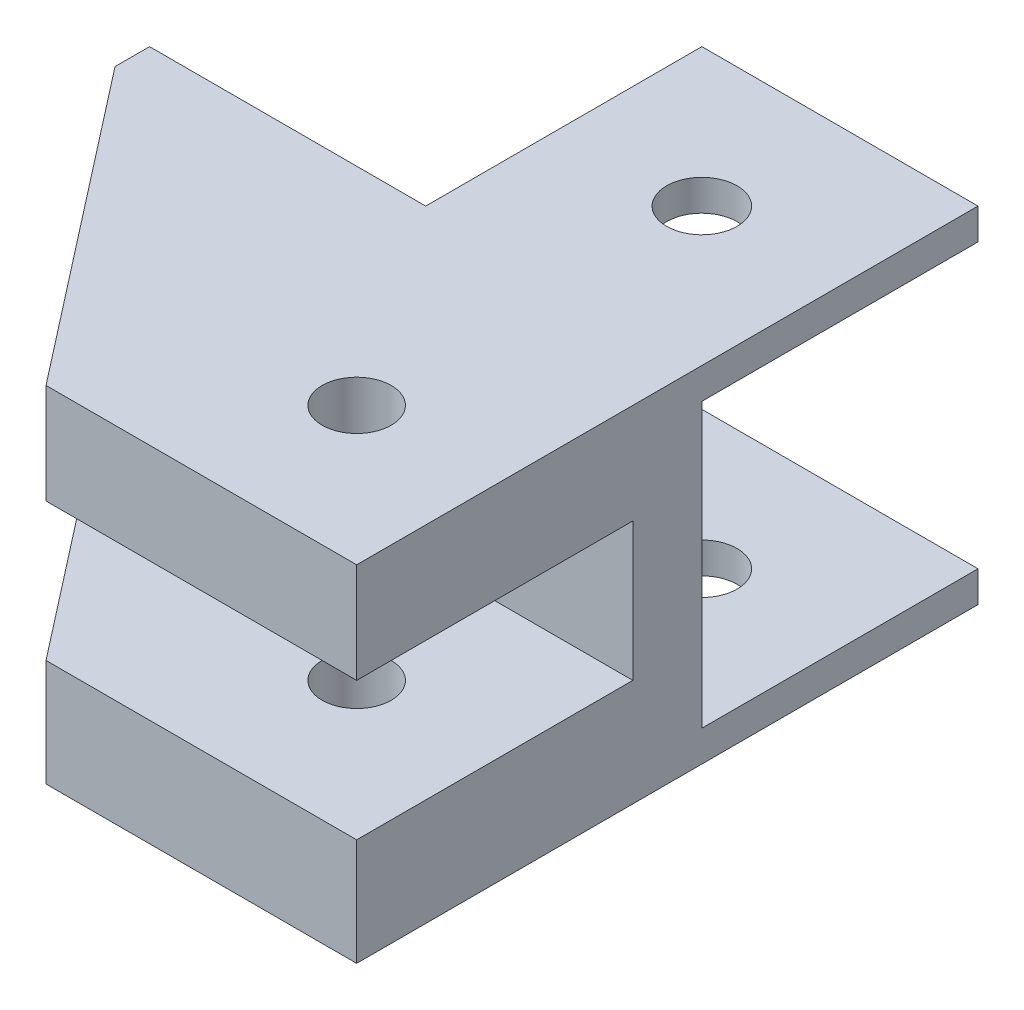
SolidWorks part; units mm, degrees
ref_plane "Front Plane" through (0, 0, 0) normal (0, 0, 1) x (1, 0, 0)
ref_plane "Top Plane" through (0, 0, 0) normal (0, 1, 0) x (1, 0, 0)
ref_plane "Right Plane" through (0, 0, 0) normal (1, 0, 0) x (0, 0, -1)
sketch "Sketch2" plane through (0, 0, 0) normal (1, 0, 0) x (0, 0, -1)
  line L1 (0, 0) -> (45, 0)
  line L2 (0, 0) -> (0, 25)
  line L3 (0, 25) -> (45, 25)
  line L4 (45, 0) -> (45, 25)
  line L8 (25, 22.75) -> (25, 2.25)
  line L9 (20, 22.75) -> (20, 2.25)
  line L10 (0, 22.75) -> (45, 22.75)
  line L11 (0, 2.25) -> (45, 2.25)
  line L12 (20, 17.75) -> (0, 17.75)
  line L13 (20, 7.75) -> (0, 7.75)
  dimension "D1" = 45
  dimension "D2" = 25
  dimension "D3" = 20
  dimension "D4" = 20
  dimension "D5" = 10
  dimension "D6" = 5
  dimension "D7" = 2.25
  dimension "D8" = 2.25
extrude "Boss-Extrude1" add sketch "Sketch2" along normal blind 20 contours L9 L11 L8 L10 | L2 L10 L4 L3 | L11 L2 L1 L4 | L12 L9 L10 L2 | L9 L13 L2 L11
sketch "Sketch3" plane through (0, 25, 0) normal (0, 1, 0) x (1, 0, 0)
  line L0 (10, 45) -> (10, 0) construction
  line L1 (0, 22.5) -> (20, 22.5) construction
  line L2 (0, 10) -> (20, 10) construction
  line L3 (20, 35) -> (0, 35) construction
  line L4 (0, 45) -> (0, 0)
  line L5 (0, 0) -> (20, 0)
  line L6 (20, 0) -> (20, 45)
  line L7 (20, 45) -> (0, 45)
  line L8 (0, 45) -> (0, 0)
  line L9 (0, 0) -> (20, 0)
  line L10 (20, 0) -> (20, 45)
  line L11 (20, 45) -> (0, 45)
  circle A0 centre (10, 10) radius 2.5
  circle A1 centre (10, 35) radius 2.55
  dimension "D3" = 5
  dimension "D5" = 5.1
  dimension "D2" = 10
  dimension "D4" = 10
  dimension "D1" = 0
extrude "Cut-Extrude1" cut sketch "Sketch3" against normal through all contours A0 | A1
sketch "Sketch5" plane through (0, 0, 0) normal (-1, 0, 0) x (0, 0, 1)
  line L0 (-25, 22.75) -> (-25, 25)
  line L1 (-25, 2.25) -> (-25, 0)
  line L12 (-20, 7.75) -> (-20, 17.75)
  line L13 (-20, 17.75) -> (0, 17.75)
  line L14 (0, 17.75) -> (0, 25)
  line L15 (0, 25) -> (-45, 25)
  line L16 (-45, 25) -> (-45, 22.75)
  line L17 (-45, 22.75) -> (-25, 22.75)
  line L18 (-25, 22.75) -> (-25, 2.25)
  line L19 (-25, 2.25) -> (-45, 2.25)
  line L20 (-45, 2.25) -> (-45, 0)
  line L21 (-45, 0) -> (0, 0)
  line L22 (0, 0) -> (0, 7.75)
  line L23 (0, 7.75) -> (-20, 7.75)
  line L24 (-20, 7.75) -> (-20, 17.75)
  line L25 (-20, 17.75) -> (0, 17.75)
  line L26 (0, 17.75) -> (0, 25)
  line L27 (0, 25) -> (-45, 25)
  line L28 (-45, 25) -> (-45, 22.75)
  line L29 (-45, 22.75) -> (-25, 22.75)
  line L30 (-25, 22.75) -> (-25, 2.25)
  line L31 (-25, 2.25) -> (-45, 2.25)
  line L32 (-45, 2.25) -> (-45, 0)
  line L33 (-45, 0) -> (0, 0)
  line L34 (0, 0) -> (0, 7.75)
  line L35 (0, 7.75) -> (-20, 7.75)
  line M13 (-20, 7.75) -> (-20, 17.75)
  line M14 (-20, 17.75) -> (0, 17.75)
  line M15 (0, 17.75) -> (0, 25)
  line M16 (0, 25) -> (-45, 25)
  line M19 (-25, 22.75) -> (-25, 2.25)
  line M22 (-45, 0) -> (0, 0)
  line M23 (0, 0) -> (0, 7.75)
  line M24 (0, 7.75) -> (-20, 7.75)
  dimension "D1" = 0
extrude "Boss-Extrude2" add sketch "Sketch5" along normal blind 20 contours L1 L0 M19 M22 M23 M24 M13 M14 M15 M16
sketch "Sketch6" plane through (0, 0, 0) normal (0, -1, 0) x (1, 0, 0)
  line L0 (0, -25) -> (0, 0) construction
  line L1 (-2.5, 0) -> (-20, -22.5)
  line L6 (20, 0) -> (-20, 0)
  line L7 (-20, 0) -> (-20, -25)
  line L8 (-20, -25) -> (0, -25)
  line L9 (0, -25) -> (0, -45)
  line L10 (0, -45) -> (20, -45)
  line L11 (20, -45) -> (20, 0)
  line L12 (20, 0) -> (-20, 0)
  line L13 (-20, 0) -> (-20, -25)
  line L14 (-20, -25) -> (0, -25)
  line L15 (0, -25) -> (0, -45)
  line L16 (0, -45) -> (20, -45)
  line L17 (20, -45) -> (20, 0)
  line M9 (20, 0) -> (-20, 0)
  line M10 (-20, 0) -> (-20, -25)
  dimension "D2" = 2.5
  dimension "D3" = 2.5
  dimension "D1" = 0
extrude "Cut-Extrude2" cut sketch "Sketch6" against normal through all contours L1 M9 M10
sketch "Sketch7" plane through (0, 0, -20) normal (0, 0, 1) x (1, 0, 0)
  line L0 (0, 24.7346) -> (0, 0) construction
  line L1 (0, 0) -> (-20, 0)
  line L2 (-10, 0) -> (-10, 25) construction
  line L9 (-2.5, 7.75) -> (-18.0556, 7.75)
  line L10 (-18.0556, 7.75) -> (-18.0556, 17.75)
  line L11 (-18.0556, 17.75) -> (-2.5, 17.75)
  line L12 (-2.5, 17.75) -> (-2.5, 25)
  line L13 (-2.5, 25) -> (-20, 25)
  line L14 (-20, 25) -> (-20, 0)
  line L15 (-20, 0) -> (-2.5, 0)
  line L16 (-2.5, 0) -> (-2.5, 7.75)
  line L17 (-2.5, 7.75) -> (-18.0556, 7.75)
  line L18 (-18.0556, 7.75) -> (-18.0556, 17.75)
  line L19 (-18.0556, 17.75) -> (-2.5, 17.75)
  line L20 (-2.5, 17.75) -> (-2.5, 25)
  line L21 (-2.5, 25) -> (-20, 25)
  line L22 (-20, 25) -> (-20, 0)
  line L23 (-20, 0) -> (-2.5, 0)
  line L24 (-2.5, 0) -> (-2.5, 7.75)
  circle A0 centre (-10, 12.5) radius 2.55
  dimension "D2" = 5.1
  dimension "D1" = 0
extrude "Cut-Extrude3" cut sketch "Sketch7" against normal blind 20 contours A0
